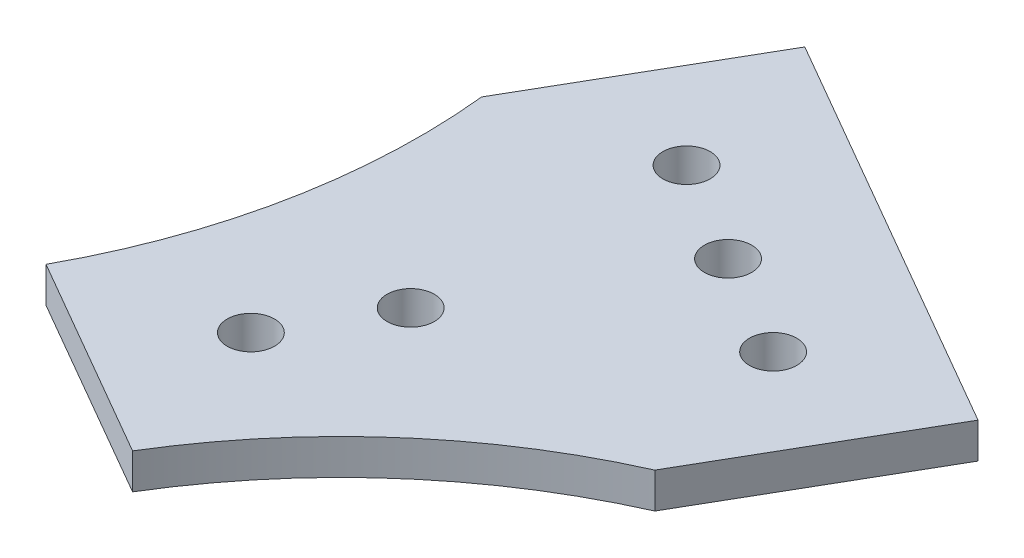
SolidWorks part; units mm, degrees
ref_plane "前视基准面" through (0, 0, 0) normal (0, 0, 1) x (1, 0, 0)
ref_plane "上视基准面" through (0, 0, 0) normal (0, 1, 0) x (1, 0, 0)
ref_plane "右视基准面" through (0, 0, 0) normal (1, 0, 0) x (0, 0, -1)
sketch "草图1" plane through (0, 0, 0) normal (0, 1, 0) x (1, 0, 0)
  line L0 (-5.3376, 6.8134) -> (4.6624, 24.1339)
  line L1 (4.6624, 24.1339) -> (-29.9787, 44.1339)
  line L2 (-29.9787, 44.1339) -> (-39.9787, 26.8134)
  line L3 (-46.1389, -3.8565) -> (-28.8184, -13.8565)
  circle A0 centre (-26.3184, 30.4737) radius 2
  circle A1 centre (-17.7134, 25.378) radius 2
  arc A2 (-5.3376, 6.8134) -> (-28.8184, -13.8565) centre (15.9889, -41.0852) ccw
  arc A3 (-46.1389, -3.8565) -> (-39.9787, 26.8134) centre (-92.1234, 21.3334) ccw
  circle A4 centre (-8.9979, 20.4737) radius 2
  circle A5 centre (-27.5339, 8.3684) radius 2
  circle A6 centre (-32.4787, -0.1962) radius 2
extrude "凸台-拉伸1" add sketch "草图1" along normal blind 3
